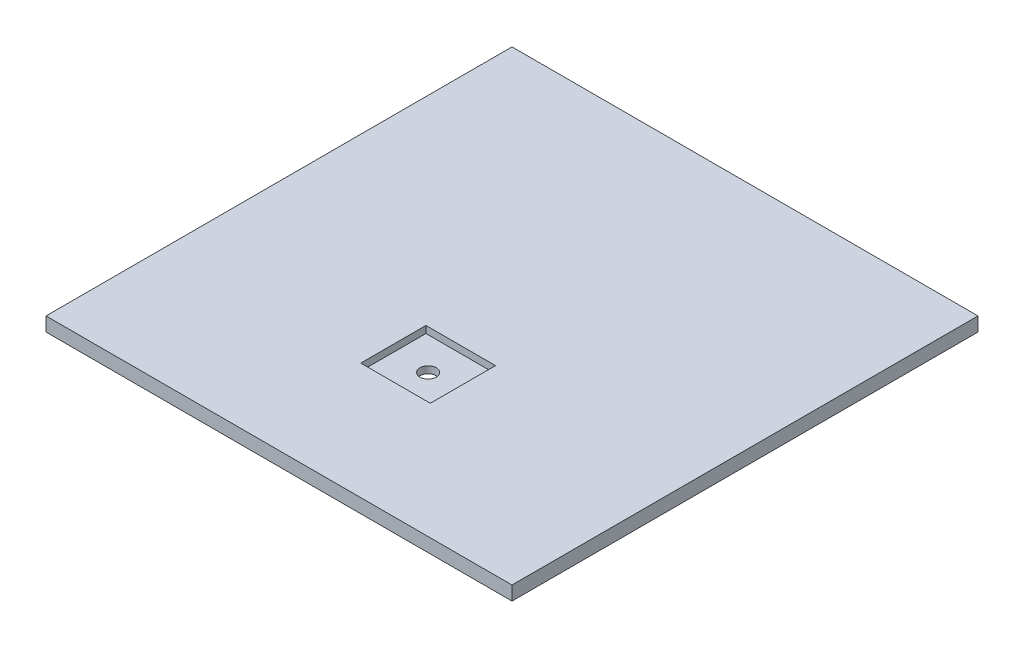
SolidWorks part; units mm, degrees
ref_plane "Front Plane" through (0, 0, 0) normal (0, 0, 1) x (1, 0, 0)
ref_plane "Top Plane" through (0, 0, 0) normal (0, 1, 0) x (1, 0, 0)
ref_plane "Right Plane" through (0, 0, 0) normal (1, 0, 0) x (0, 0, -1)
sketch "Sketch1" plane through (0, 0, 0) normal (0, 1, 0) x (1, 0, 0)
  line L0 (12.9538, 58.3852) -> (12.9538, -9.6148) construction
  line L1 (-37.0462, 58.3852) -> (62.9538, 58.3852)
  line L2 (-37.0462, 58.3852) -> (-37.0462, -41.6148)
  line L3 (-37.0462, -41.6148) -> (62.9538, -41.6148)
  line L4 (62.9538, 58.3852) -> (62.9538, -41.6148)
  line L5 (-37.0462, 8.3852) -> (62.9538, 8.3852) construction
  circle A0 centre (12.9538, -9.6148) radius 1.75
  point P9 (-1.4748, -28.9353)
  point P10 (-1.2898, -33.0989)
  dimension "D4" = 3.5
  dimension "D1" = 100
  dimension "D2" = 100
  dimension "D3" = 32
extrude "Boss-Extrude1" add sketch "Sketch1" along normal blind 3
sketch "Sketch2" plane through (0, 3, 0) normal (0, 1, 0) x (1, 0, 0)
  line L0 (12.9538, -2.6189) -> (12.9538, -16.6106) construction
  line L1 (5.4915, -2.6189) -> (20.416, -2.6189)
  line L2 (5.4915, -2.6189) -> (5.4915, -16.6106)
  line L3 (5.4915, -16.6106) -> (20.416, -16.6106)
  line L4 (20.416, -2.6189) -> (20.416, -16.6106)
  line L5 (5.4915, -9.6148) -> (20.416, -9.6148) construction
  line L6 (-37.0462, -41.6148) -> (62.9538, -41.6148) construction
  circle A0 centre (12.9538, -9.6148) radius 1.75 construction
  point P8 (0, 0)
  point P11 (12.9538, -9.6148)
  point P14 (0, 0)
  point P15 (12.9538, -41.6148)
  dimension "D1" = 13.9917
  dimension "D2" = 14.9245
extrude "Cut-Extrude1" cut sketch "Sketch2" against normal blind 1.5
